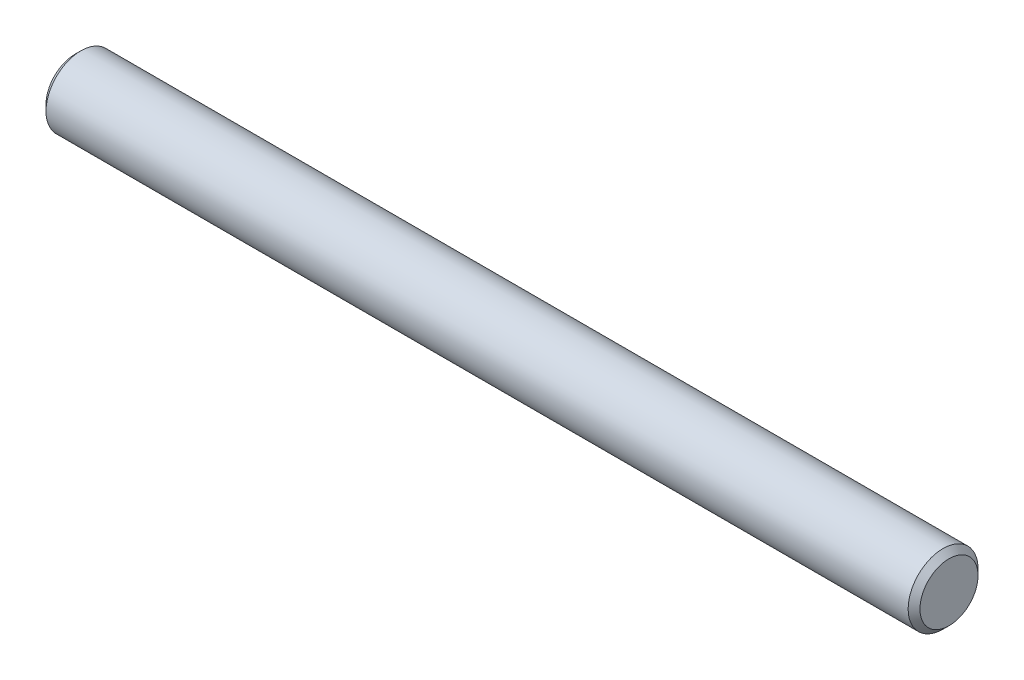
SolidWorks part; units mm, degrees
ref_plane "前视基准面" through (0, 0, 0) normal (0, 0, 1) x (1, 0, 0)
ref_plane "上视基准面" through (0, 0, 0) normal (0, 1, 0) x (1, 0, 0)
ref_plane "右视基准面" through (0, 0, 0) normal (1, 0, 0) x (0, 0, -1)
sketch "草图1" plane through (0, 0, 0) normal (0, 0, 1) x (1, 0, 0)
  line L0 (-50, 0) -> (-50, 3.3235)
  line L1 (-50, 3.3235) -> (-49.3235, 4)
  line L2 (-49.3235, 4) -> (49.3235, 4)
  line L3 (49.3235, 4) -> (50, 3.3235)
  line L4 (50, 3.3235) -> (50, 0)
  line L5 (50, 0) -> (-50, 0)
  line L6 (50, 0) -> (-50, 0) construction
revolve "旋转1" add sketch "草图1" angle 360 about L6
cosmetic thread "装饰螺纹线1" parameters "D1"=100, "D2"=6.647
ref_plane "基准面1" through (-50, 0, 0) normal (1, 0, 0) x (0, 0, -1)
